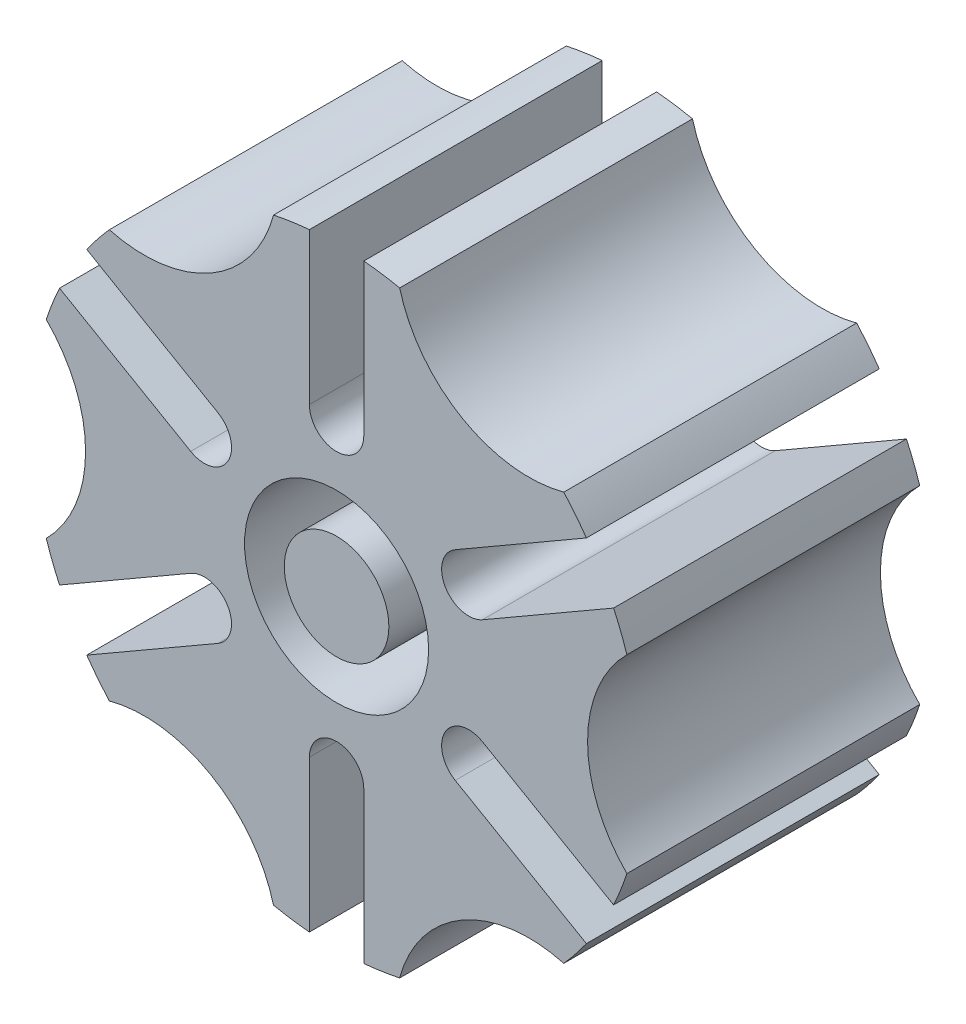
SolidWorks part; units mm, degrees
ref_plane "Plano frontal" through (0, 0, 0) normal (0, 0, 1) x (1, 0, 0)
ref_plane "Plano superior" through (0, 0, 0) normal (0, 1, 0) x (1, 0, 0)
ref_plane "Plano direito" through (0, 0, 0) normal (1, 0, 0) x (0, 0, -1)
sketch "Esboço1" plane through (0, 0, 0) normal (0, 0, 1) x (1, 0, 0)
  line L0 (0, 0) -> (0, 73) construction
  line L1 (6.5, 36.5) -> (6.5, 72.71)
  line L2 (6.5, 0) -> (6.5, 73) construction
  line L3 (0, 0) -> (79.6743, 46) construction
  line L4 (0, 0) -> (46, 79.6743) construction
  line L5 (28.3599, 23.8792) -> (59.7187, 41.9842)
  line L6 (34.8599, 12.6208) -> (66.2187, 30.7259)
  line L7 (34.8599, -12.6208) -> (66.2187, -30.7259)
  line L8 (28.3599, -23.8792) -> (59.7187, -41.9842)
  line L9 (6.5, -36.5) -> (6.5, -72.71)
  line L10 (-6.5, -36.5) -> (-6.5, -72.71)
  line L11 (-28.3599, -23.8792) -> (-59.7187, -41.9842)
  line L12 (-34.8599, -12.6208) -> (-66.2187, -30.7259)
  line L13 (-34.8599, 12.6208) -> (-66.2187, 30.7259)
  line L14 (-28.3599, 23.8792) -> (-59.7187, 41.9842)
  line L15 (-6.5, 36.5) -> (-6.5, 72.71)
  line L16 (-3, 12.1347) -> (-3, 15)
  line L17 (-3, 15) -> (3, 15)
  line L18 (3, 12.1347) -> (3, 15)
  circle A0 centre (0, 0) radius 12.5
  circle A1 centre (0, 0) radius 22
  circle A2 centre (0, 0) radius 38 construction
  circle A3 centre (0, 0) radius 73 construction
  arc A4 (0, 30) -> (6.4299, 37.4521) centre (0, 36.5) ccw
  circle A5 centre (0, 0) radius 92 construction
  arc A6 (15.0816, 71.4251) -> (54.3152, 48.7736) centre (46, 79.6743) ccw
  arc A7 (25.9808, 15) -> (29.2195, 24.2945) centre (31.6099, 18.25) cw
  arc A8 (6.5, 72.71) -> (15.0816, 71.4251) centre (0, 0) cw
  arc A9 (59.7187, 41.9842) -> (54.3152, 48.7736) centre (0, 0) ccw
  arc A10 (25.9808, 15) -> (35.6494, 13.1576) centre (31.6099, 18.25) ccw
  arc A11 (66.2187, 30.7259) -> (69.3967, 22.6515) centre (0, 0) cw
  arc A12 (69.3967, 22.6515) -> (69.3967, -22.6515) centre (92, 0) ccw
  arc A13 (66.2187, -30.7259) -> (69.3967, -22.6515) centre (0, 0) ccw
  arc A14 (25.9808, -15) -> (35.6494, -13.1576) centre (31.6099, -18.25) cw
  arc A15 (25.9808, -15) -> (29.2195, -24.2945) centre (31.6099, -18.25) ccw
  arc A16 (59.7187, -41.9842) -> (54.3152, -48.7736) centre (0, 0) cw
  arc A17 (54.3152, -48.7736) -> (15.0816, -71.4251) centre (46, -79.6743) ccw
  arc A18 (6.5, -72.71) -> (15.0816, -71.4251) centre (0, 0) ccw
  arc A19 (0, -30) -> (6.4299, -37.4521) centre (0, -36.5) cw
  arc A20 (0, -30) -> (-6.4299, -37.4521) centre (0, -36.5) ccw
  arc A21 (-6.5, -72.71) -> (-15.0816, -71.4251) centre (0, 0) cw
  arc A22 (-15.0816, -71.4251) -> (-54.3152, -48.7736) centre (-46, -79.6743) ccw
  arc A23 (-59.7187, -41.9842) -> (-54.3152, -48.7736) centre (0, 0) ccw
  arc A24 (-25.9808, -15) -> (-29.2195, -24.2945) centre (-31.6099, -18.25) cw
  arc A25 (-25.9808, -15) -> (-35.6494, -13.1576) centre (-31.6099, -18.25) ccw
  arc A26 (-66.2187, -30.7259) -> (-69.3967, -22.6515) centre (0, 0) cw
  arc A27 (-69.3967, -22.6515) -> (-69.3967, 22.6515) centre (-92, 0) ccw
  arc A28 (-66.2187, 30.7259) -> (-69.3967, 22.6515) centre (0, 0) ccw
  arc A29 (-25.9808, 15) -> (-35.6494, 13.1576) centre (-31.6099, 18.25) cw
  arc A30 (-25.9808, 15) -> (-29.2195, 24.2945) centre (-31.6099, 18.25) ccw
  arc A31 (-59.7187, 41.9842) -> (-54.3152, 48.7736) centre (0, 0) cw
  arc A32 (-54.3152, 48.7736) -> (-15.0816, 71.4251) centre (-46, 79.6743) ccw
  arc A33 (-6.5, 72.71) -> (-15.0816, 71.4251) centre (0, 0) ccw
  arc A34 (0, 30) -> (-6.4299, 37.4521) centre (0, 36.5) cw
  point P93 (0, 0)
  point P96 (0, 15)
  dimension "D1" = 25
  dimension "D2" = 44
  dimension "D3" = 76
  dimension "D4" = 146
  dimension "D6" = 184
  dimension "D9" = 64
  dimension "D7" = 60
  dimension "D8" = 30
  dimension "D11" = 6
  dimension "D12" = 27.5
  dimension "D5" = 6.5
  dimension "D10" = 6
extrude "Ressalto-extrusão1" add sketch "Esboço1" along normal blind 64 and the other way blind 6 contours A4 A34 L15 A33 A32 A31 L14 A30 A29 L13 A28 A27 A26 L12 A25 A24 L11 A23 A22 A21 L10 A20 A19 L9 A18 A17 A16 L8 A15 A14 L7 A13 A12 A11 L6 A10 A7 L5 A9 A6 A8 L1 A1 | A0
